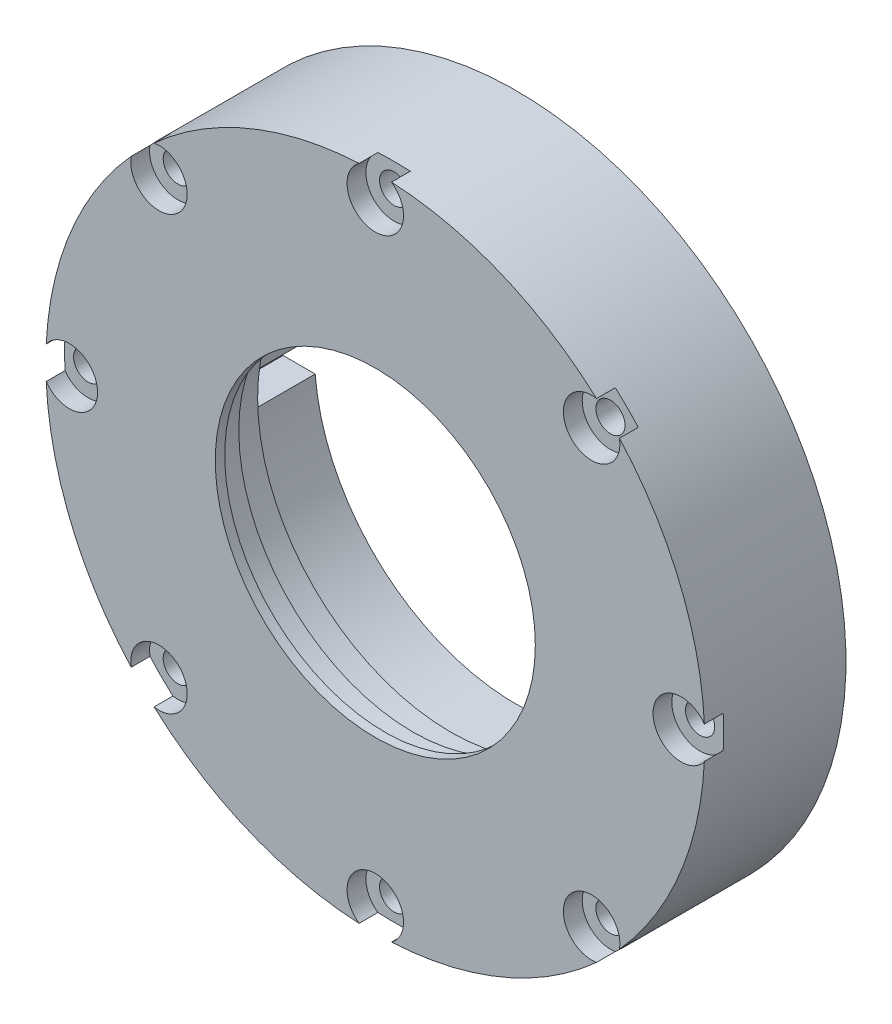
SolidWorks part; units mm, degrees
ref_plane "前视基准面" through (0, 0, 0) normal (0, 0, 1) x (1, 0, 0)
ref_plane "上视基准面" through (0, 0, 0) normal (0, 1, 0) x (1, 0, 0)
ref_plane "右视基准面" through (0, 0, 0) normal (1, 0, 0) x (0, 0, -1)
other "Configuration Table"
sketch "草图1" plane through (0, 0, 0) normal (0, 0, 1) x (1, 0, 0)
  circle A0 centre (0, 0) radius 35
  circle A1 centre (0, 0) radius 18.5
extrude "凸台-拉伸1" add sketch "草图1" along normal blind 3
sketch "草图5" plane through (0, 0, 3) normal (0, 0, 1) x (1, 0, 0)
  circle A0 centre (0, 0) radius 17
  circle A1 centre (0, 0) radius 35
  dimension "D1" = 34
  dimension "D2" = 70
extrude "凸台-拉伸3" add sketch "草图5" along normal blind 1
sketch "草图7" plane through (0, 0, 0) normal (0, 0, -1) x (-1, 0, 0)
  circle A0 centre (0, 0) radius 21.45
  circle A1 centre (0, 0) radius 35
  dimension "D1" = 42.9
  dimension "D2" = 70
extrude "凸台-拉伸4" add sketch "草图7" along normal blind 4
sketch "草图9" plane through (0, 0, -4) normal (0, 0, -1) x (-1, 0, 0)
  line L0 (0, 0) -> (24.8, 0)
  line L1 (24.8, -1.75) -> (24.8, 1.75)
  line L2 (24.8, 1.75) -> (21.3825, 1.75)
  line L3 (24.8, -1.75) -> (21.3825, -1.75)
  line L4 (-24.8, -1.75) -> (-21.3825, -1.75)
  line L5 (-24.8, 1.75) -> (-24.8, -1.75)
  line L6 (-24.8, 1.75) -> (-21.3825, 1.75)
  circle A0 centre (0, 0) radius 21.454
  point P14 (0, 0)
  circle M3 centre (0, 0) radius 35
  dimension "D1" = 24.8
  dimension "D2" = 1.75
  dimension "D3" = 2
extrude "凸台-拉伸6" add sketch "草图9" along normal blind 7 contours A0 L2 L1 L3 L4 L5 L6 M3
sketch "草图12" plane through (0, 0, 4) normal (0, 0, 1) x (1, 0, 0)
  line L0 (0, 0) -> (32.5, 0)
  circle A0 centre (32.5, 0) radius 1.55
  circle A1 centre (0, -32.5) radius 1.55
  circle A2 centre (-32.5, 0) radius 1.55
  circle A3 centre (0, 32.5) radius 1.55
  circle A4 centre (22.981, 22.981) radius 1.55
  circle A5 centre (32.5, 0) radius 1.55
  circle A6 centre (22.981, -22.981) radius 1.55
  circle A7 centre (0, -32.5) radius 1.55
  circle A8 centre (-22.981, -22.981) radius 1.55
  circle A9 centre (-32.5, 0) radius 1.55
  circle A10 centre (-22.981, 22.981) radius 1.55
  point P13 (0, 0)
  point P27 (0, 0)
  dimension "D2" = 4
  dimension "D1" = 32.5
  dimension "D3" = 8
extrude "切除-拉伸1" cut sketch "草图12" against normal through all contours A3 | A2 | A1 | A0
sketch "草图13" plane through (0, 0, 4) normal (0, 0, 1) x (1, 0, 0)
  circle A0 centre (0, 32.5) radius 3
  circle A1 centre (32.5, 0) radius 3
  circle A2 centre (0, -32.5) radius 3
  circle A3 centre (-32.5, 0) radius 3
  point P12 (0, 0)
  dimension "D1" = 4
extrude "切除-拉伸2" cut sketch "草图13" against normal blind 2
sketch "草图15" plane through (0, 0, 4) normal (0, 0, 1) x (1, 0, 0)
  line L0 (0, 0) -> (0, 32.5)
  line L1 (0, 0) -> (22.981, 22.981)
  circle A0 centre (22.981, 22.981) radius 1.55
  circle A1 centre (22.981, -22.981) radius 1.55
  circle A2 centre (-22.981, -22.981) radius 1.55
  circle A3 centre (-22.981, 22.981) radius 1.55
  point P15 (0, 0)
  dimension "D3" = 4
  dimension "D1" = 32.5
  dimension "D2" = 45
extrude "切除-拉伸3" cut sketch "草图15" against normal through all
sketch "草图16" plane through (0, 0, 4) normal (0, 0, 1) x (1, 0, 0)
  circle A0 centre (22.981, 22.981) radius 3
  circle A1 centre (22.981, -22.981) radius 3
  circle A2 centre (-22.981, -22.981) radius 3
  circle A3 centre (-22.981, 22.981) radius 3
  point P12 (0, 0)
  dimension "D1" = 4
extrude "切除-拉伸4" cut sketch "草图16" against normal blind 2
sketch "草图17" plane through (0, 0, 0) normal (0, 0, -1) x (-1, 0, 0)
  circle A0 centre (0, 0) radius 21.45
  circle A1 centre (0, 0) radius 20.5
extrude "凸台-拉伸7" add sketch "草图17" along normal blind 4
